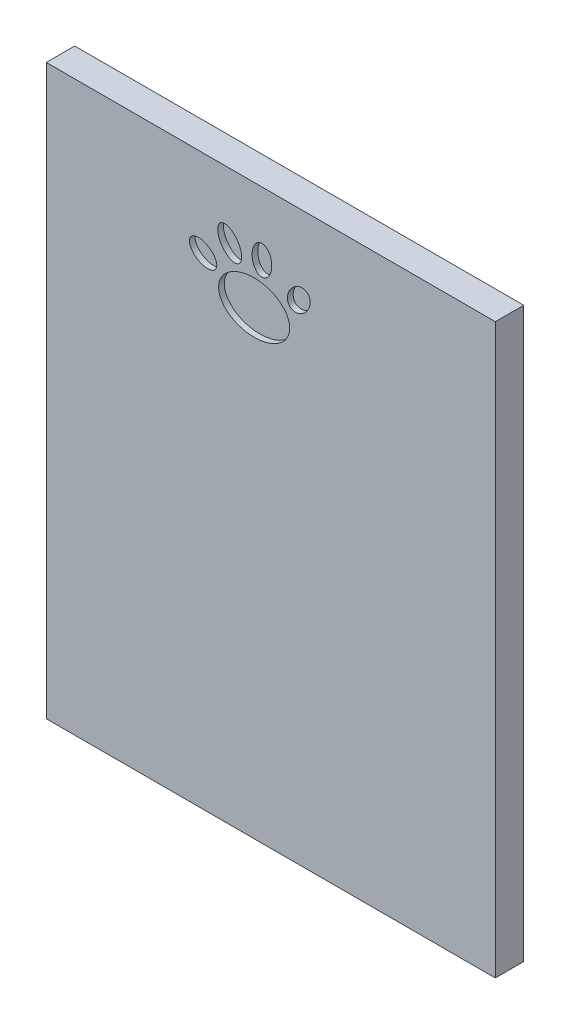
SolidWorks part; units mm, degrees
ref_plane "前基準面" through (0, 0, 0) normal (0, 0, 1) x (1, 0, 0)
ref_plane "上基準面" through (0, 0, 0) normal (0, 1, 0) x (1, 0, 0)
ref_plane "右基準面" through (0, 0, 0) normal (1, 0, 0) x (0, 0, -1)
sketch "草圖1" plane through (0, 0, 0) normal (0, 0, 1) x (1, 0, 0)
  line L1 (0, 0) -> (158, 0)
  line L2 (0, 0) -> (0, 200)
  line L3 (0, 200) -> (158, 200)
  line L4 (158, 0) -> (158, 200)
  dimension "D1" = 158
  dimension "D2" = 200
extrude "填料-伸長1" add sketch "草圖1" along normal blind 10
sketch "草圖2" plane through (0, 0, 10) normal (0, 0, 1) x (1, 0, 0)
  ellipse E0 centre (73.1438, 161.8891) end of major axis (85.6547, 161.8891) minor radius 9.0504
  ellipse E1 centre (55.1756, 169.5084) end of major axis (59.6792, 166.9439) minor radius 3.4523
  ellipse E2 centre (64.549, 177.1679) end of major axis (67.6068, 172.4266) minor radius 3.4523
  ellipse E3 centre (75.8801, 177.6501) end of major axis (75.8801, 182.7918) minor radius 3.4523
  ellipse E4 centre (88.8715, 172.0082) end of major axis (85.928, 168.2815) minor radius 3.4523
  point P7 (48.1436, 173.5041)
  point P19 (59.302, 181.2269)
  point P26 (0, 0)
  point P27 (75.8801, 172.5084)
  point P34 (83.9342, 170.9396)
extrude "除料-伸長1" cut sketch "草圖2" against normal blind 2
